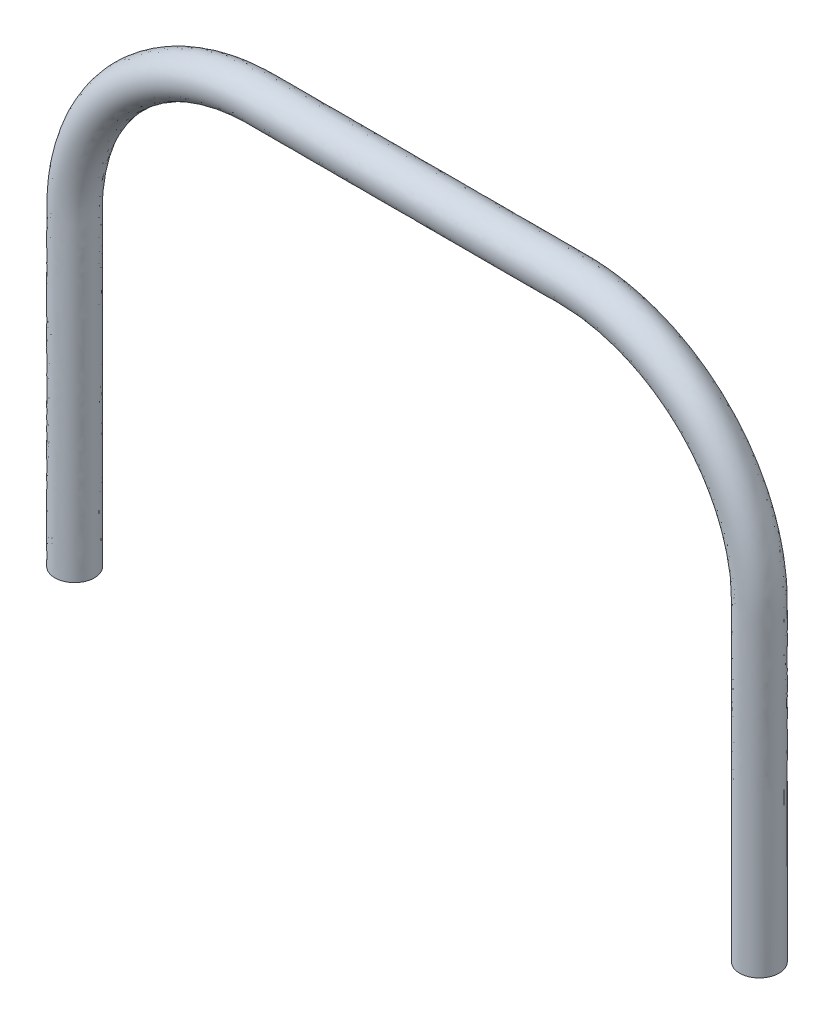
SolidWorks part; units mm, degrees
ref_plane "Plan de face" through (0, 0, 0) normal (0, 0, 1) x (1, 0, 0)
ref_plane "Plan de dessus" through (0, 0, 0) normal (0, 1, 0) x (1, 0, 0)
ref_plane "Plan de droite" through (0, 0, 0) normal (1, 0, 0) x (0, 0, -1)
sketch "Esquisse2" plane through (0, 0, 0) normal (0, 0, 1) x (1, 0, 0)
  line L0 (0, 0) -> (60.169, 0) construction
  line L1 (0, 0) -> (0, 64.9665) construction
  line L2 (0, 0) -> (0, 250)
  line L3 (150, 400) -> (400, 400)
  line L4 (550, 250) -> (550, 0)
  arc A0 (400, 400) -> (550, 250) centre (400, 250) cw
  arc A1 (0, 250) -> (150, 400) centre (150, 250) cw
  point P0 (112.1421, 0)
  point P12 (0, 400)
  dimension "D1" = 150
  dimension "D2" = 250
  dimension "D3" = 250
sweep "Balayage1" add path "Esquisse2" circular profile diameter 31.75 parameters "D3"=31.75
